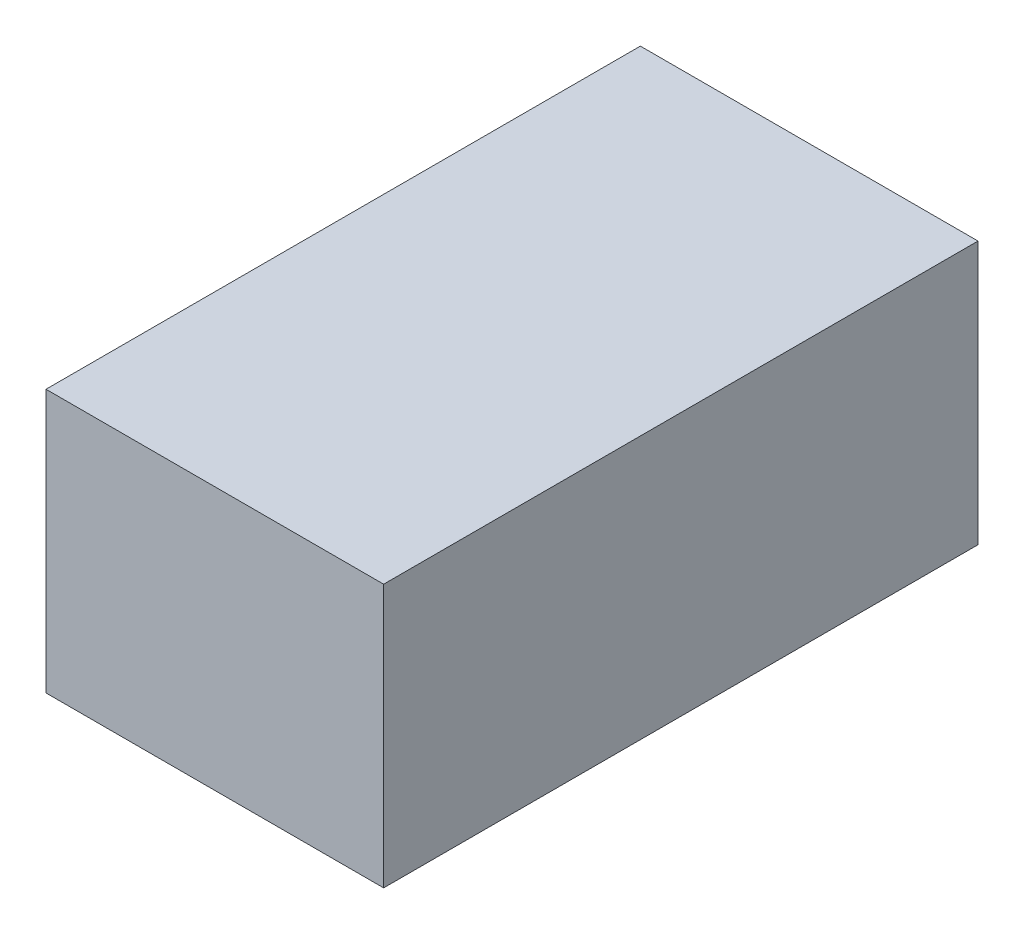
SolidWorks part; units mm, degrees
ref_plane "Front Plane" through (0, 0, 0) normal (0, 0, 1) x (1, 0, 0)
ref_plane "Top Plane" through (0, 0, 0) normal (0, 1, 0) x (1, 0, 0)
ref_plane "Right Plane" through (0, 0, 0) normal (1, 0, 0) x (0, 0, -1)
sketch "Sketch1" plane through (0, 0, 0) normal (0, 0, 1) x (1, 0, 0)
  line L1 (-13.35, -10.4) -> (13.35, -10.4)
  line L2 (-13.35, -10.4) -> (-13.35, 10.4)
  line L3 (-13.35, 10.4) -> (13.35, 10.4)
  line L4 (13.35, -10.4) -> (13.35, 10.4)
  line L5 (-13.35, -10.4) -> (13.35, 10.4) construction
  line L6 (-13.35, 10.4) -> (13.35, -10.4) construction
  point P0 (0, 0)
  dimension "D1" = 20.8
  dimension "D2" = 26.7
extrude "Boss-Extrude1" add sketch "Sketch1" along normal blind 47
